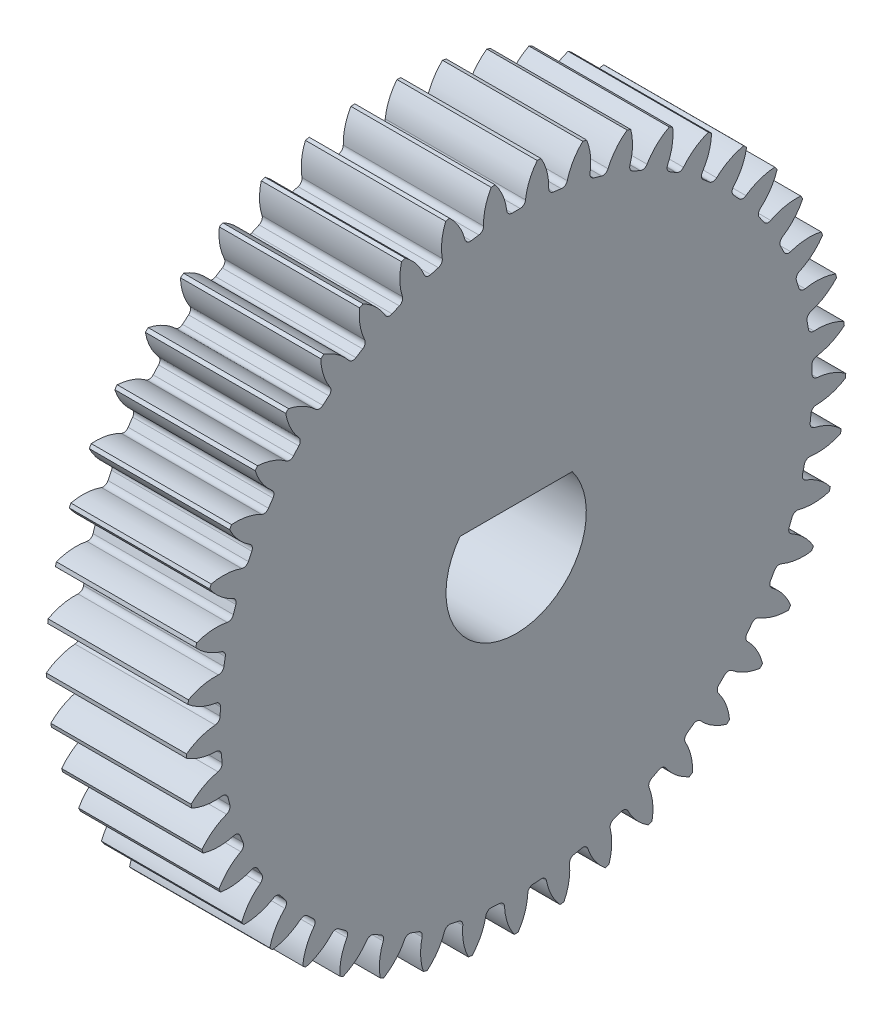
SolidWorks part; units mm, degrees
ref_plane "Front Plane" through (0, 0, 0) normal (0, 0, 1) x (1, 0, 0)
ref_plane "Top Plane" through (0, 0, 0) normal (0, 1, 0) x (1, 0, 0)
ref_plane "Right Plane" through (0, 0, 0) normal (1, 0, 0) x (0, 0, -1)
sketch "Sketch1" plane through (0, 0, 0) normal (1, 0, 0) x (0, 0, -1)
  circle A0 centre (0, 0) radius 5
  circle A1 centre (0, 0) radius 23.5
  dimension "D1" = 10
  dimension "D2" = 47
extrude "Boss-Extrude2" add sketch "Sketch1" along normal blind 10
sketch "Sketch3" plane through (10, 0, 0) normal (1, 0, 0) x (0, 0, -1)
  line L0 (0, 0) -> (0, 23.5) construction
  line L1 (-0.6413, 21.0903) -> (0, 0) construction
  line L2 (0, 19.9188) -> (-0.7652, 22.0211) construction
  circle A0 centre (0, 0) radius 23.5 construction
  arc A1 (0.6413, 21.0903) -> (-0.6413, 21.0903) centre (0, 0) ccw
  arc A2 (0.9354, 22.4805) -> (-0.9354, 22.4805) centre (0, 0) ccw construction
  arc A3 (1.5009, 23.452) -> (-1.5009, 23.452) centre (0, 0) ccw
  arc A4 (-1.5009, 23.452) -> (-0.6413, 21.0903) centre (-4.6505, 20.9683) cw
  arc A5 (1.5009, 23.452) -> (0.6413, 21.0903) centre (4.6505, 20.9683) ccw
  point P17 (-0.8813, 22.3402)
  dimension "D1" = 47
  dimension "D2" = 45
  dimension "D3" = 2.4
  dimension "D4" = 20
  dimension "D5" = 1.8708
extrude "Cut-Extrude1" cut sketch "Sketch3" against normal through all
fillet "Fillet1" radius 0.38 2 edges at (5, 21.0903, -0.6413) (5, 21.0903, 0.6413)
pattern_circular "CirPattern2" count 45 over 360 about axis through (0, 0, 0) along (1, 0, 0) of "Fillet1", "Cut-Extrude1"
sketch "Sketch4" plane through (10, 0, 0) normal (1, 0, 0) x (0, 0, -1)
  line L0 (-4, 3) -> (4, 3)
  circle A0 centre (0, 0) radius 5 construction
  arc A1 (-4, 3) -> (4, 3) centre (0, 0) cw
  dimension "D1" = 3
extrude "Boss-Extrude3" add sketch "Sketch4" against normal blind 10
equation "\"No of teeth\"= 45"
equation "\"Module\"= 1"
equation "\"Outer Diameter\"= ( \"No of teeth\" + 2 ) * \"Module\""
equation "\"Pitch Diameter\"= \"No of teeth\" * \"Module\""
equation "\"Backlash\"= 0.3 * \"Module\""
equation "\"Arc Length\"= ( ( \"Module\" * pi ) / 2 ) + \"Backlash\""
equation "\"Fillet Radius\"= 0.38 * \"Module\""
equation "\"Bore Diameter\"=10"
equation "\"Presseure angle\"= 20"
equation "\"Tooth Design\"= IIF ( \"Module\" <= 1.25 , 2.4 * \"Module\" , 2.25 * \"Module\" )"
equation "\"D1@Sketch1\"=\"Bore Diameter\""
equation "\"D2@Sketch1\"=\"Outer Diameter\""
equation "\"D1@Sketch3\"=\"Outer Diameter\""
equation "\"D2@Sketch3\"=\"Pitch Diameter\""
equation "\"D3@Sketch3\"=\"Tooth Design\""
equation "\"D4@Sketch3\"=\"Presseure angle\""
equation "\"D5@Sketch3\"=\"Arc Length\""
equation "\"D1@Fillet1\"=\"Fillet Radius\""
equation "\"D1@CirPattern2\"=\"No of teeth\""
